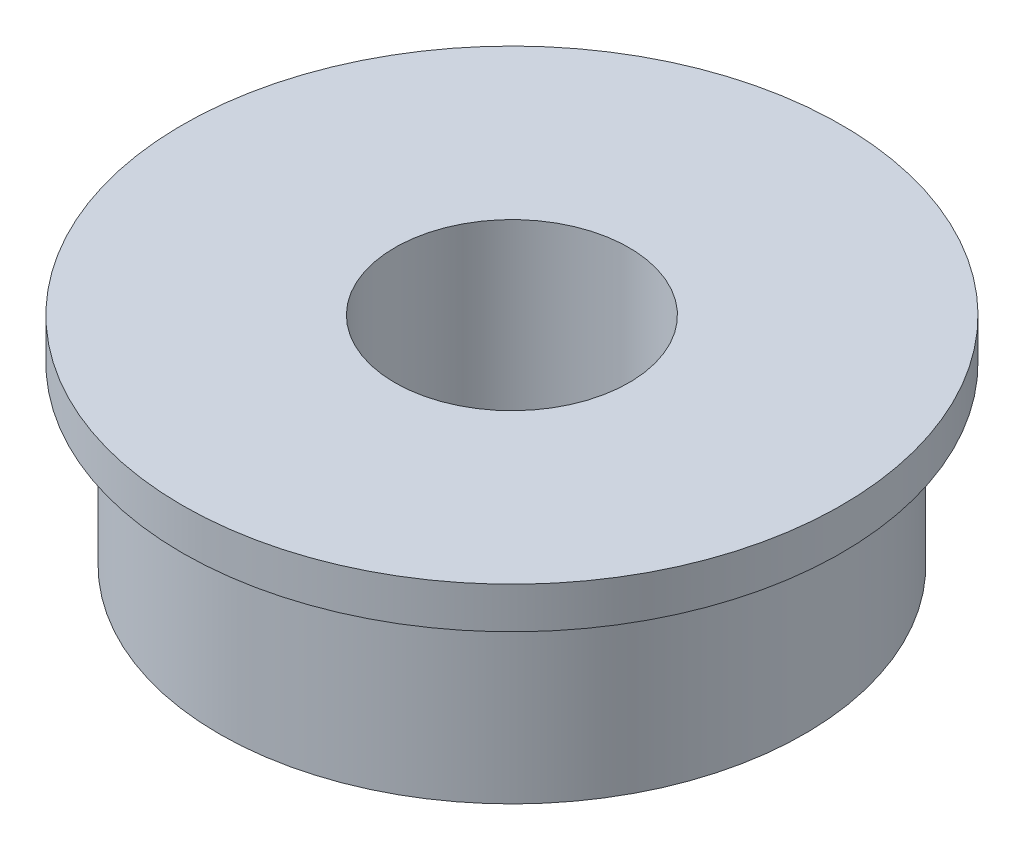
SolidWorks part; units mm, degrees
ref_plane "Front" through (0, 0, 0) normal (0, 0, 1) x (1, 0, 0)
ref_plane "Top" through (0, 0, 0) normal (0, 1, 0) x (1, 0, 0)
ref_plane "Right" through (0, 0, 0) normal (1, 0, 0) x (0, 0, -1)
sketch "Sketch1" plane through (0, 0, 0) normal (0, 1, 0) x (1, 0, 0)
  circle A0 centre (0, 0) radius 7.9375
  circle A1 centre (0, 0) radius 3.175
  dimension "D1" = 15.875
  dimension "D2" = 6.35
extrude "Boss-Extrude1" add sketch "Sketch1" along normal blind 4.7498
sketch "Sketch2" plane through (0, 4.7498, 0) normal (0, 1, 0) x (1, 0, 0)
  circle A0 centre (0, 0) radius 8.9375
  circle A1 centre (0, 0) radius 3.175
  circle A2 centre (0, 0) radius 3.175 construction
  dimension "D1" = 17.875
extrude "Boss-Extrude2" add sketch "Sketch2" along normal blind 1.1176
